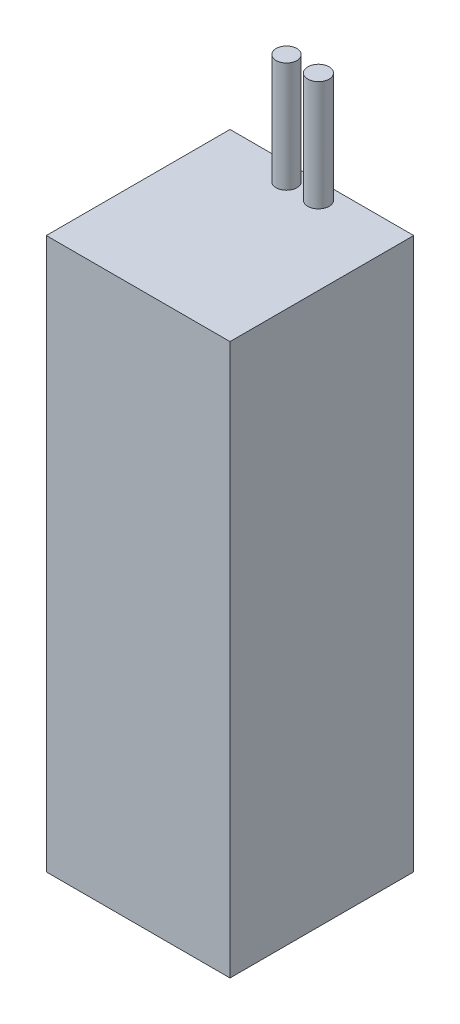
SolidWorks part; units mm, degrees
ref_plane "Front Plane" through (0, 0, 0) normal (0, 0, 1) x (1, 0, 0)
ref_plane "Top Plane" through (0, 0, 0) normal (0, 1, 0) x (1, 0, 0)
ref_plane "Right Plane" through (0, 0, 0) normal (1, 0, 0) x (0, 0, -1)
sketch "Sketch1" plane through (0, 0, 0) normal (0, 1, 0) x (1, 0, 0)
  line L1 (0, 0) -> (50, 0)
  line L2 (0, 0) -> (0, 50)
  line L3 (0, 50) -> (50, 50)
  line L4 (50, 0) -> (50, 50)
  dimension "D1" = 50
  dimension "D2" = 50
extrude "Boss-Extrude1" add sketch "Sketch1" along normal blind 150
sketch "Sketch2" plane through (0, 150, 0) normal (0, 1, 0) x (1, 0, 0)
  circle A0 centre (20.0201, 45.3544) radius 2.8336
  circle A1 centre (28.7152, 45.3544) radius 2.9
extrude "Boss-Extrude2" add sketch "Sketch2" along normal blind 30
